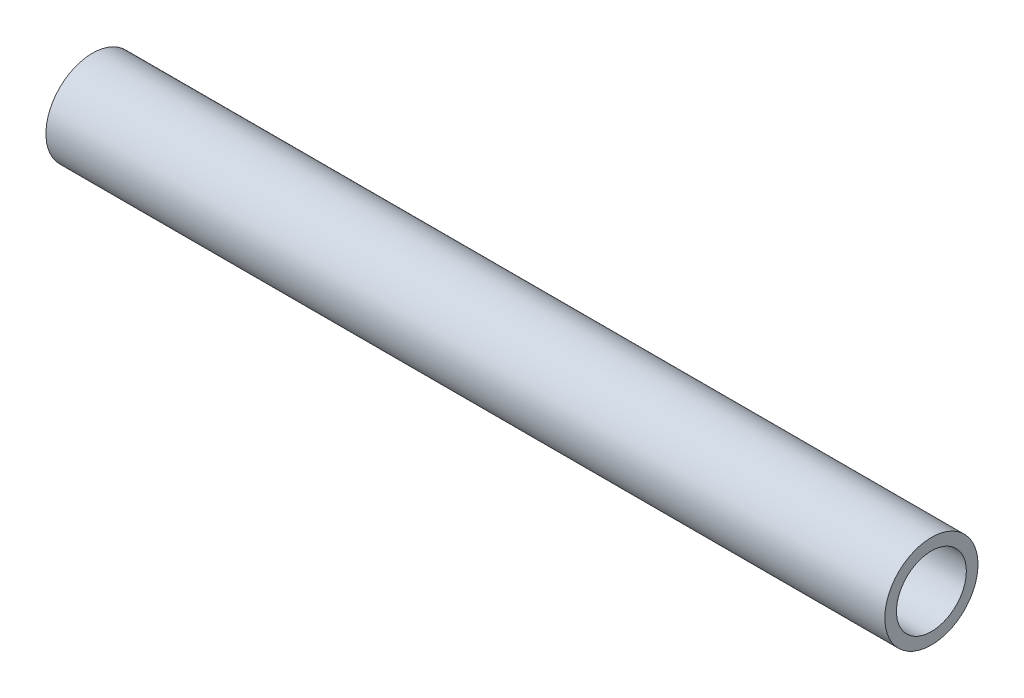
SolidWorks part; units mm, degrees
ref_plane "前视基准面" through (0, 0, 0) normal (0, 0, 1) x (1, 0, 0)
ref_plane "上视基准面" through (0, 0, 0) normal (0, 1, 0) x (1, 0, 0)
ref_plane "右视基准面" through (0, 0, 0) normal (1, 0, 0) x (0, 0, -1)
other "Configuration Table"
sketch "草图1" plane through (0, 0, 0) normal (1, 0, 0) x (0, 0, -1)
  circle A0 centre (0, 0) radius 1.5
  circle A1 centre (0, 0) radius 2
extrude "凸台-拉伸1" add sketch "草图1" along normal blind 36
